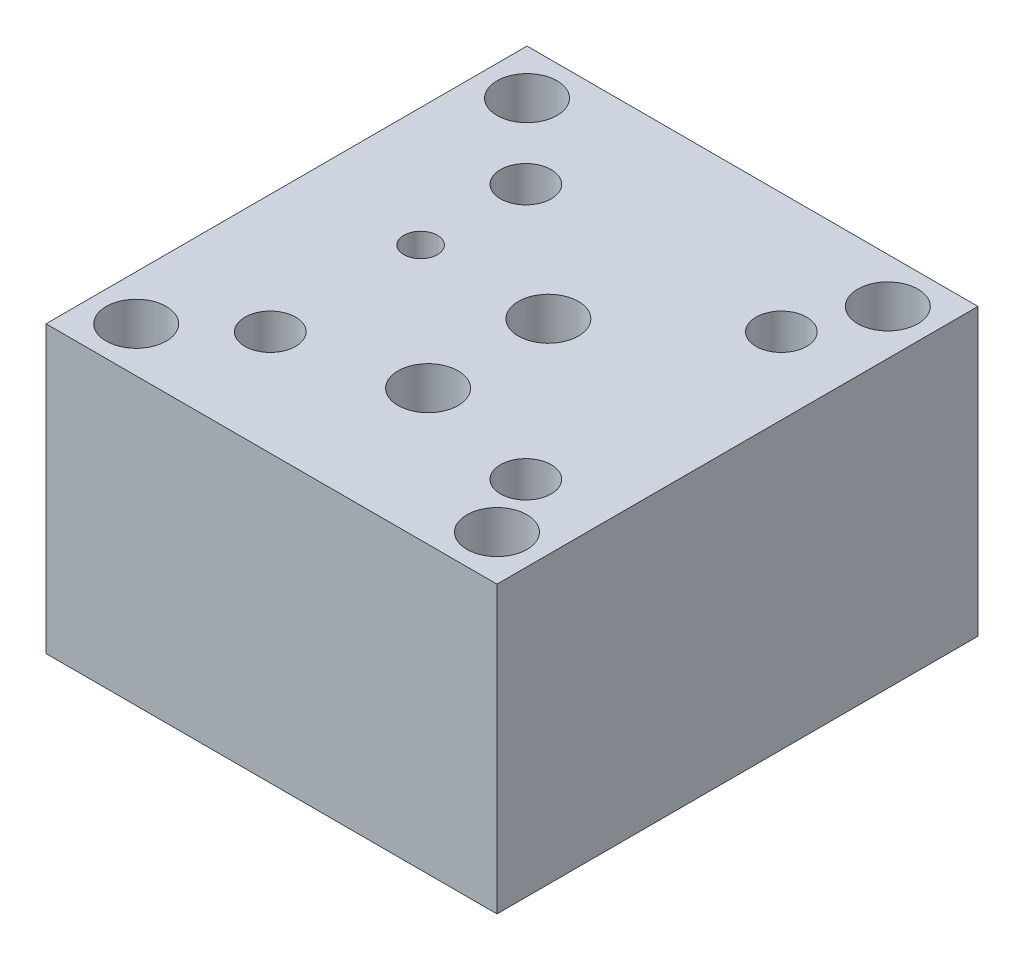
SolidWorks part; units mm, degrees
ref_plane "Front Plane" through (0, 0, 0) normal (0, 0, 1) x (1, 0, 0)
ref_plane "Top Plane" through (0, 0, 0) normal (0, 1, 0) x (1, 0, 0)
ref_plane "Right Plane" through (0, 0, 0) normal (1, 0, 0) x (0, 0, -1)
sketch "Sketch1" plane through (0, 0, 0) normal (0, 1, 0) x (1, 0, 0)
  line L1 (-47.625, -50.8) -> (47.625, -50.8)
  line L2 (-47.625, -50.8) -> (-47.625, 50.8)
  line L3 (-47.625, 50.8) -> (47.625, 50.8)
  line L4 (47.625, -50.8) -> (47.625, 50.8)
  line L5 (-47.625, -50.8) -> (47.625, 50.8) construction
  line L6 (-47.625, 50.8) -> (47.625, -50.8) construction
  point P0 (0, 0)
  dimension "D1" = 47.625
  dimension "D2" = 50.8
extrude "Boss-Extrude1" add sketch "Sketch1" along normal mid plane 60.325
sketch "Sketch2" plane through (0, 0, 0) normal (0, 1, 0) x (1, 0, 0)
  circle A0 centre (-38.1, -41.275) radius 4.3688
  circle A1 centre (38.1, -41.275) radius 4.3688
  circle A2 centre (-38.1, 41.275) radius 4.3688
  circle A3 centre (38.1, 41.275) radius 4.3688
  point P8 (0, 0)
  dimension "D1" = 8.7376
  dimension "D2" = 8.7376
  dimension "D3" = 8.7376
  dimension "D4" = 8.7376
  dimension "D5" = 76.2
  dimension "D6" = 82.55
  dimension "D7" = 38.1
  dimension "D8" = 41.275
extrude "Cut-Extrude2" cut sketch "Sketch2" against normal blind 85.725 from offset 30.1625
sketch "Sketch3" plane through (0, 0, 0) normal (0, 1, 0) x (1, 0, 0)
  circle A0 centre (-38.1, -41.275) radius 6.35
  circle A1 centre (38.1, -41.275) radius 6.35
  circle A2 centre (-38.1, 41.275) radius 6.35
  circle A3 centre (38.1, 41.275) radius 6.35
  point P8 (0, 0)
  dimension "D1" = 12.7
  dimension "D2" = 12.7
  dimension "D3" = 12.7
  dimension "D4" = 12.7
  dimension "D5" = 76.2
  dimension "D6" = 82.55
  dimension "D7" = 38.1
  dimension "D8" = 41.275
extrude "Cut-Extrude4" cut sketch "Sketch3" against normal blind 25.4 from offset 30.1625
sketch "Sketch4" plane through (0, 0, 0) normal (0, 1, 0) x (1, 0, 0)
  circle A0 centre (-22.479, -28.575) radius 5.3578
  circle A1 centre (31.496, -28.575) radius 5.3578
  circle A2 centre (-22.479, 25.4) radius 5.3578
  circle A3 centre (31.496, 25.4) radius 5.3578
  point P8 (0, 0)
  dimension "D1" = 10.7156
  dimension "D2" = 10.7156
  dimension "D3" = 10.7156
  dimension "D4" = 10.7156
  dimension "D5" = 53.975
  dimension "D6" = 53.975
  dimension "D7" = 22.479
  dimension "D8" = 28.575
extrude "Cut-Extrude6" cut sketch "Sketch4" against normal blind 20.32 from offset 30.1625
sketch "Sketch5" plane through (0, 0, 0) normal (0, 1, 0) x (1, 0, 0)
  circle A0 centre (4.5085, -22.225) radius 6.35
  circle A1 centre (4.5085, 3.175) radius 6.35
  point P4 (0, 0)
  dimension "D1" = 12.7
  dimension "D2" = 12.7
  dimension "D3" = 25.4
  dimension "D4" = 4.5085
  dimension "D5" = 22.225
extrude "Cut-Extrude8" cut sketch "Sketch5" against normal blind 45.72 from offset 30.1625
sketch "Sketch6" plane through (0, 0, 0) normal (0, 1, 0) x (1, 0, 0)
  circle A0 centre (-22.479, 3.175) radius 3.556
  point P2 (0, 0)
  dimension "D1" = 7.112
  dimension "D2" = 22.479
  dimension "D3" = 3.175
extrude "Cut-Extrude10" cut sketch "Sketch6" against normal blind 7.9375 from offset 30.1625
sketch "Sketch7" plane through (0, 0, 0) normal (1, 0, 0) x (0, 0, -1)
  circle A0 centre (-16.637, -11.1125) radius 5.5562
  point P2 (0, 0)
  dimension "D1" = 11.1125
  dimension "D2" = 16.637
  dimension "D3" = 11.1125
extrude "Cut-Extrude12" cut sketch "Sketch7" along normal blind 53.34 from offset 47.625
sketch "Sketch8" plane through (0, 0, 0) normal (0, 0, 1) x (1, 0, 0)
  circle A0 centre (10.16, -11.1125) radius 5.5562
  point P2 (0, 0)
  dimension "D1" = 11.1125
  dimension "D2" = 10.16
  dimension "D3" = 11.1125
extrude "Cut-Extrude14" cut sketch "Sketch8" along normal blind 53.34 from offset 50.8
sketch "Sketch9" plane through (0, 0, 0) normal (0, 1, 0) x (1, 0, 0)
  circle A0 centre (-28.575, -11.1125) radius 6.35
  circle A1 centre (15.875, 30.1625) radius 6.35
  point P4 (0, 0)
  dimension "D1" = 12.7
  dimension "D2" = 12.7
  dimension "D3" = 44.45
  dimension "D4" = 41.275
  dimension "D5" = 28.575
  dimension "D6" = 11.1125
extrude "Cut-Extrude16" cut sketch "Sketch9" along normal blind 27.94 from offset 30.1625
sketch "Sketch10" plane through (0, 0, 0) normal (0, 1, 0) x (1, 0, 0)
  circle A0 centre (-28.575, -11.1125) radius 12.7127
  circle A1 centre (15.875, 30.1625) radius 12.7127
  point P4 (0, 0)
  dimension "D1" = 25.4254
  dimension "D2" = 25.4254
  dimension "D3" = 44.45
  dimension "D4" = 41.275
  dimension "D5" = 28.575
  dimension "D6" = 11.1125
extrude "Cut-Extrude18" cut sketch "Sketch10" along normal blind 3.1242 from offset 30.1625
